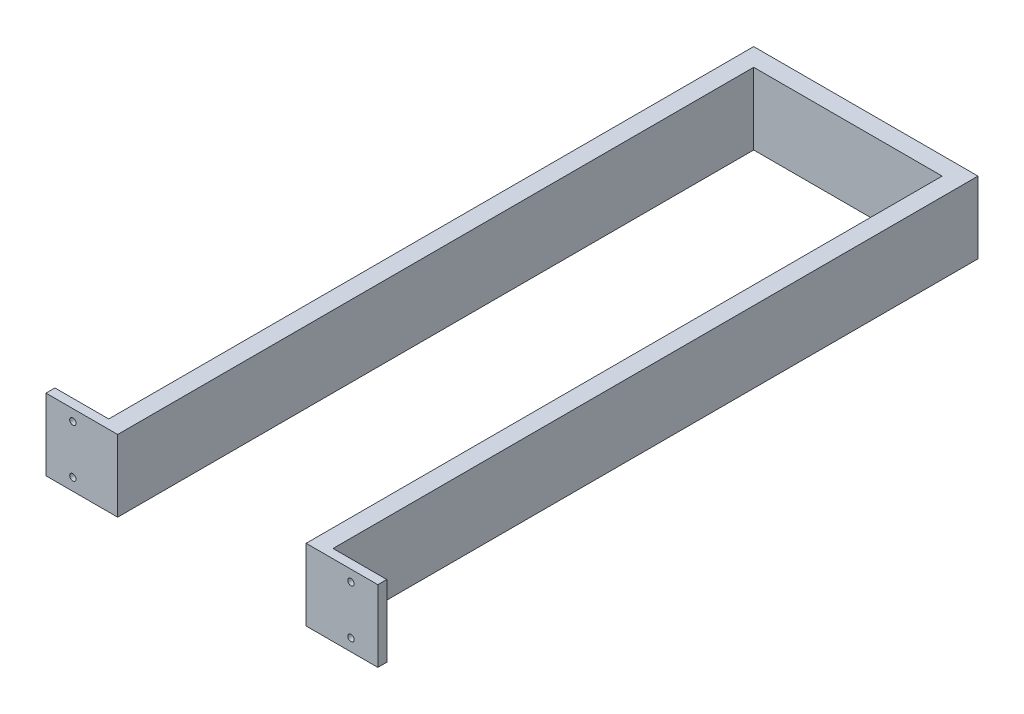
SolidWorks part; units mm, degrees
ref_plane "Front Plane" through (0, 0, 0) normal (0, 0, 1) x (1, 0, 0)
ref_plane "Top Plane" through (0, 0, 0) normal (0, 1, 0) x (1, 0, 0)
ref_plane "Right Plane" through (0, 0, 0) normal (1, 0, 0) x (0, 0, -1)
sketch "Sketch1" plane through (0, 0, 0) normal (0, 0, 1) x (1, 0, 0)
  line L0 (-12.7, 3.2147) -> (6.35, 3.2147) construction
  line L1 (-12.7, 12.7) -> (12.7, 12.7)
  line L2 (-12.7, 12.7) -> (-12.7, -12.7)
  line L3 (-12.7, -12.7) -> (12.7, -12.7)
  line L4 (12.7, 12.7) -> (12.7, -12.7)
  line L5 (-12.7, 12.7) -> (12.7, -12.7) construction
  line L6 (-12.7, -12.7) -> (12.7, 12.7) construction
  line L7 (12.7, -12.7) -> (6.35, -12.7)
  line L8 (12.7, -12.7) -> (12.7, 12.7)
  line L9 (12.7, 12.7) -> (6.35, 12.7)
  line L10 (6.35, -12.7) -> (6.35, 12.7)
  point P0 (0, 0)
  point P10 (-3.175, 3.2147)
  point P11 (46.0885, 6.6288)
  point P12 (-3.175, 0.1767)
  point P13 (-3.175, 8.7466)
  point P14 (-3.175, -8.3932)
  point P15 (-3.175, -8.3932)
  point P16 (-3.175, 9.3601)
  point P17 (0, 0)
  point P18 (0, 0)
  point P19 (0, 0)
  point P20 (0, 0)
  point P21 (0, 0)
  point P22 (0, 0)
  point P23 (0, 0)
  point P24 (0, 0)
  point P25 (0, 0)
  point P26 (0, 0)
  dimension "D1" = 25.4
  dimension "D2" = 25.4
  dimension "D3" = 6.35
  dimension "D4" = 8.5699
  dimension "D5" = 8.5699
extrude "Boss-Extrude1" add sketch "Sketch1" along normal blind 3.175 contours L1 L4 L3 L2
sketch "Sketch3" plane through (0, 0, 0) normal (0, 0, -1) x (-1, 0, 0)
  line L0 (12.7, 12.7) -> (-12.7, 12.7) construction
  line L1 (-12.7, -12.7) -> (-6.35, -12.7)
  line L2 (-12.7, -12.7) -> (-12.7, 12.7)
  line L3 (-12.7, 12.7) -> (-6.35, 12.7)
  line L4 (-6.35, -12.7) -> (-6.35, 12.7)
  line L6 (2.7925, 12.7) -> (2.7925, -12.7) construction
  line L7 (12.7, -12.7) -> (-12.7, -12.7) construction
  line L8 (-6.35, 0) -> (12.7, 0) construction
  line L9 (12.7, 12.7) -> (12.7, -12.7) construction
  line L10 (12.7, 7.5911) -> (-6.35, 7.5911) construction
  line L11 (12.7, -9.5487) -> (-6.35, -9.5487) construction
  point P7 (2.7925, -0.9788)
  point P8 (2.7925, -9.5487)
  point P10 (2.7925, 7.5911)
  point P22 (0, 0)
  point P23 (0, 0)
  dimension "D1" = 6.35
  dimension "D2" = 8.5699
  dimension "D3" = 8.5699
extrude "Boss-Extrude2" add sketch "Sketch3" along normal blind 228.6
hole_wizard "#4-40 Tapped Hole1" positions "Sketch5" profile "Sketch6" tap size "#4-40" standard "ANSI Inch" end condition through all
sketch "Sketch5" plane through (0, 0, 0) normal (0, 0, -1) x (-1, 0, 0)
  point P0 (3.175, 8.7466)
  point P2 (3.175, -8.3932)
  point P5 (3.175, 8.7466)
  point P7 (3.175, -8.3932)
sketch "Sketch6" plane through (-3.175, 8.7466, 0) normal (1, 0, 0) x (0, 1, 0)
  line L0 (0, 0) -> (0, 3.175)
  line L1 (0, 3.175) -> (1.1303, 3.175)
  line L2 (1.1303, 3.175) -> (1.1303, 0)
  line L5 (1.1303, 0) -> (0, 0)
  line L11 (0, -6.35) -> (0, 107.95) construction
  dimension "Thru Tap Drill Dia." = 2.2606
  dimension "Thru Tap Drill Depth" = 3.175
sketch "Sketch7" plane through (12.7, 0, 0) normal (1, 0, 0) x (0, 0, -1)
  line L0 (-3.175, -12.7) -> (228.6, -12.7) construction
  line L1 (228.6, 12.7) -> (222.25, 12.7)
  line L2 (228.6, 12.7) -> (228.6, -12.7)
  line L3 (228.6, -12.7) -> (222.25, -12.7)
  line L4 (222.25, 12.7) -> (222.25, -12.7)
  dimension "D1" = 6.35
extrude "Boss-Extrude3" add sketch "Sketch7" along normal blind 73.152 contours L4 L3 L2 L1
ref_plane "Plane5" through (46.101, 0, 0) normal (-1, 0, 0) x (0, 0, 1)
sketch "Sketch9" plane through (0, 0, -222.25) normal (0, 0, 1) x (1, 0, 0)
  line L0 (85.852, 12.7) -> (12.7, 12.7) construction
  line L1 (85.852, -12.7) -> (79.502, -12.7)
  line L2 (85.852, -12.7) -> (85.852, 12.7)
  line L3 (85.852, 12.7) -> (79.502, 12.7)
  line L4 (79.502, -12.7) -> (79.502, 12.7)
  dimension "D1" = 6.35
extrude "Boss-Extrude4" add sketch "Sketch9" along normal blind 222.25 contours L4 L3 L2 L1
sketch "Sketch10" plane through (0, 0, 0) normal (0, 0, 1) x (1, 0, 0)
  line L0 (79.502, 12.7) -> (12.7, 12.7) construction
  line L1 (85.852, -12.7) -> (60.452, -12.7)
  line L2 (85.852, -12.7) -> (85.852, 12.7)
  line L3 (85.852, 12.7) -> (60.452, 12.7)
  line L4 (60.452, -12.7) -> (60.452, 12.7)
  line L5 (79.502, -12.7) -> (79.502, 12.7) construction
  line L6 (79.502, -12.7) -> (79.502, 12.7) construction
  line L8 (79.502, -12.7) -> (104.902, -12.7)
  line L9 (79.502, -12.7) -> (79.502, 12.7)
  line L10 (79.502, 12.7) -> (104.902, 12.7)
  line L11 (104.902, -12.7) -> (104.902, 12.7)
  point P7 (69.972, 0)
  point P8 (77.0458, -4.838)
  point P11 (79.502, 0)
  point P12 (77.0458, 4.838)
  point P18 (79.502, -12.7)
  point P189 (95.382, 0)
  point P192 (164.0128, 8.57)
  point P194 (164.0128, -8.57)
  point P199 (99.518, -7.3533)
  dimension "D1" = 25.4
  dimension "D2" = 9.53
  dimension "D3" = 8.57
  dimension "D4" = 8.57
  dimension "D5" = 25.4
  dimension "D6" = 9.53
  dimension "D8" = 13.666
extrude "Boss-Extrude5" add sketch "Sketch10" along normal blind 3.175 contours L10 L11 L8 L9
sketch "Sketch14" plane through (0, 0, 3.175) normal (0, 0, 1) x (1, 0, 0)
  line L1 (79.502, -12.7) -> (104.902, -12.7) construction
  line L2 (79.502, 12.7) -> (85.852, 12.7)
  line L3 (79.502, 12.7) -> (79.502, -12.7)
  line L4 (79.502, -12.7) -> (85.852, -12.7)
  line L5 (85.852, 12.7) -> (85.852, -12.7)
  line L6 (-2.0447, 8.7466) -> (95.382, 8.7466)
  line L8 (-2.0447, -8.3932) -> (95.382, -8.3932)
  circle A0 centre (-3.175, 8.7466) radius 1.1303 construction
  circle A1 centre (-3.175, -8.3932) radius 1.1303 construction
  point P0 (95.382, 0.2995)
  point P1 (79.502, 12.7)
  point P9 (100.4841, -6.5863)
  point P10 (100.4841, 7.1853)
  point P16 (95.382, 8.7466)
  point P25 (95.382, -8.3932)
  point P29 (100.4841, 7.1853)
  dimension "D1" = 6.35
  dimension "D2" = 9.53
  dimension "D3" = 8.57
  dimension "D4" = 8.57
hole_wizard "#4-40 Tapped Hole4" positions "Sketch14" profile "Sketch15" tap size "#4-40" standard "ANSI Inch"
sketch "Sketch15" plane through (100.4841, 7.1853, 3.175) normal (1, 0, 0) x (0, -1, 0)
  line L0 (0, 0) -> (0, 231.775)
  line L1 (0, 231.775) -> (1.1303, 231.775)
  line L2 (1.1303, 231.775) -> (1.1303, 0)
  line L5 (1.1303, 0) -> (0, 0)
  line L11 (0, -6.35) -> (0, 107.95) construction
  dimension "Thru Tap Drill Dia." = 2.2606
  dimension "Thru Tap Drill Depth" = 231.775
sketch "Sketch16" plane through (0, 0, 3.175) normal (0, 0, 1) x (1, 0, 0)
  circle A0 centre (100.4841, 7.1853) radius 1.1303
extrude "Boss-Extrude6" add sketch "Sketch16" against normal blind 3.175
